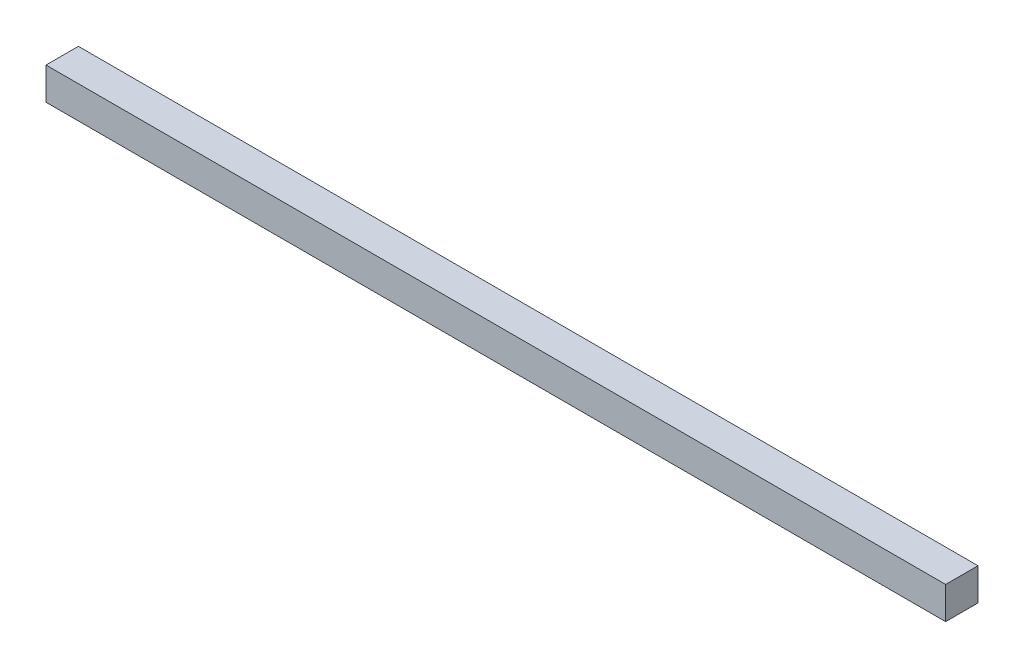
SolidWorks part; units mm, degrees
ref_plane "前视基准面" through (0, 0, 0) normal (0, 0, 1) x (1, 0, 0)
ref_plane "上视基准面" through (0, 0, 0) normal (0, 1, 0) x (1, 0, 0)
ref_plane "右视基准面" through (0, 0, 0) normal (1, 0, 0) x (0, 0, -1)
other "Configuration Table"
sketch "草图1" plane through (0, 0, 0) normal (1, 0, 0) x (0, 0, -1)
  line L1 (-5.1007, -5.0814) -> (5.1007, -5.0814)
  line L2 (-5.1007, -5.0814) -> (-5.1007, 5.0814)
  line L3 (-5.1007, 5.0814) -> (5.1007, 5.0814)
  line L4 (5.1007, -5.0814) -> (5.1007, 5.0814)
  line L5 (-5.1007, -5.0814) -> (5.1007, 5.0814) construction
  line L6 (-5.1007, 5.0814) -> (5.1007, -5.0814) construction
  point P0 (0, 0)
extrude "凸台-拉伸1" add sketch "草图1" along normal blind 240 and the other way blind 43.5
